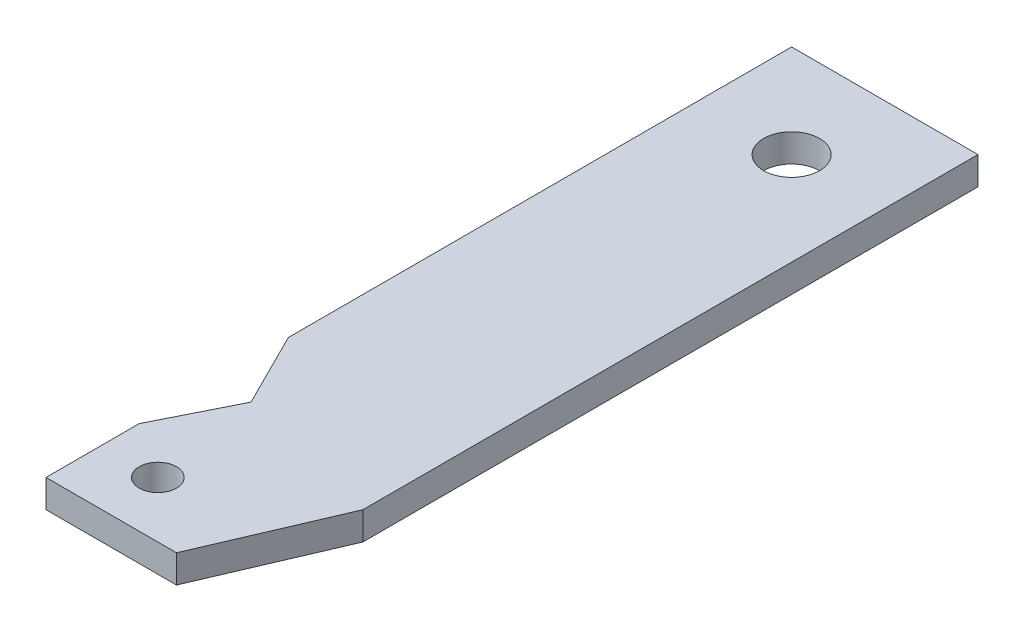
SolidWorks part; units mm, degrees
ref_plane "Plan de face" through (0, 0, 0) normal (0, 0, 1) x (1, 0, 0)
ref_plane "Plan de dessus" through (0, 0, 0) normal (0, 1, 0) x (1, 0, 0)
ref_plane "Plan de droite" through (0, 0, 0) normal (1, 0, 0) x (0, 0, -1)
sketch "Esquisse1" plane through (0, 0, 0) normal (0, 0, 1) x (1, 0, 0)
  line L1 (-12.7726, 11.5904) -> (-2.7726, 11.5904)
  line L2 (-12.7726, 11.5904) -> (-12.7726, 10.0904)
  line L3 (-12.7726, 10.0904) -> (-2.7726, 10.0904)
  line L4 (-2.7726, 11.5904) -> (-2.7726, 10.0904)
  dimension "D1" = 10
  dimension "D2" = 1.5
extrude "Extrusion1" add sketch "Esquisse1" along normal blind 40
sketch "Esquisse2" plane through (0, 11.5904, 0) normal (0, 1, 0) x (-1, 0, 0)
  line L0 (2.7726, 40) -> (2.7726, 0) construction
  line L1 (2.7726, 40) -> (12.7726, 40) construction
  line L2 (2.7726, 0) -> (12.7726, 0) construction
  line L3 (12.7726, 35) -> (10.7726, 31)
  line L4 (12.7726, 40) -> (12.7726, 0) construction
  line L5 (10.7726, 31) -> (12.7726, 27)
  line L6 (12.7726, 27) -> (12.7726, 35)
  line L7 (5.7726, 40) -> (2.7726, 40)
  line L8 (2.7726, 40) -> (2.7726, 33)
  line L9 (2.7726, 33) -> (5.7726, 40)
  circle A0 centre (9.7726, 37) radius 1
  circle A1 centre (7.7726, 5) radius 1.5
  dimension "D1" = 7
  dimension "D3" = 5
  dimension "D2" = 3
  dimension "D4" = 5
  dimension "D5" = 8
  dimension "D6" = 5
  dimension "D7" = 2
  dimension "D8" = 4
  dimension "D9" = 3
  dimension "D10" = 7
extrude "Extrusion2" cut sketch "Esquisse2" against normal blind 50
